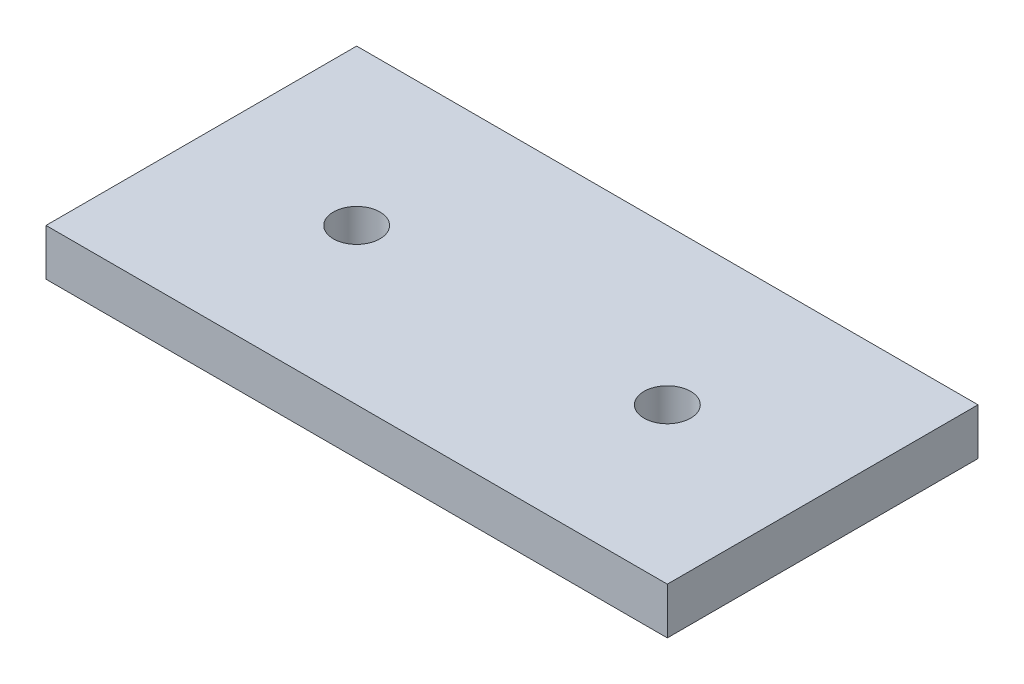
SolidWorks part; units mm, degrees
ref_plane "前视基准面" through (0, 0, 0) normal (0, 0, 1) x (1, 0, 0)
ref_plane "上视基准面" through (0, 0, 0) normal (0, 1, 0) x (1, 0, 0)
ref_plane "右视基准面" through (0, 0, 0) normal (1, 0, 0) x (0, 0, -1)
sketch "草图1" plane through (0, 0, 0) normal (0, 1, 0) x (1, 0, 0)
  line L0 (0, 0) -> (-20, 0) construction
  line L1 (-20, 10) -> (20, 10)
  line L2 (-20, 10) -> (-20, -10)
  line L3 (-20, -10) -> (20, -10)
  line L4 (20, 10) -> (20, -10)
  line L5 (-20, 10) -> (20, -10) construction
  line L6 (-20, -10) -> (20, 10) construction
  line L7 (0, 0) -> (20, 0) construction
  circle A0 centre (-10, 0) radius 1.5
  circle A1 centre (10, 0) radius 1.5
  point P0 (0, 0)
  dimension "D3" = 3
  dimension "D4" = 3
  dimension "D1" = 20
  dimension "D2" = 40
  dimension "D5" = 20
extrude "凸台-拉伸1" add sketch "草图1" along normal blind 3
